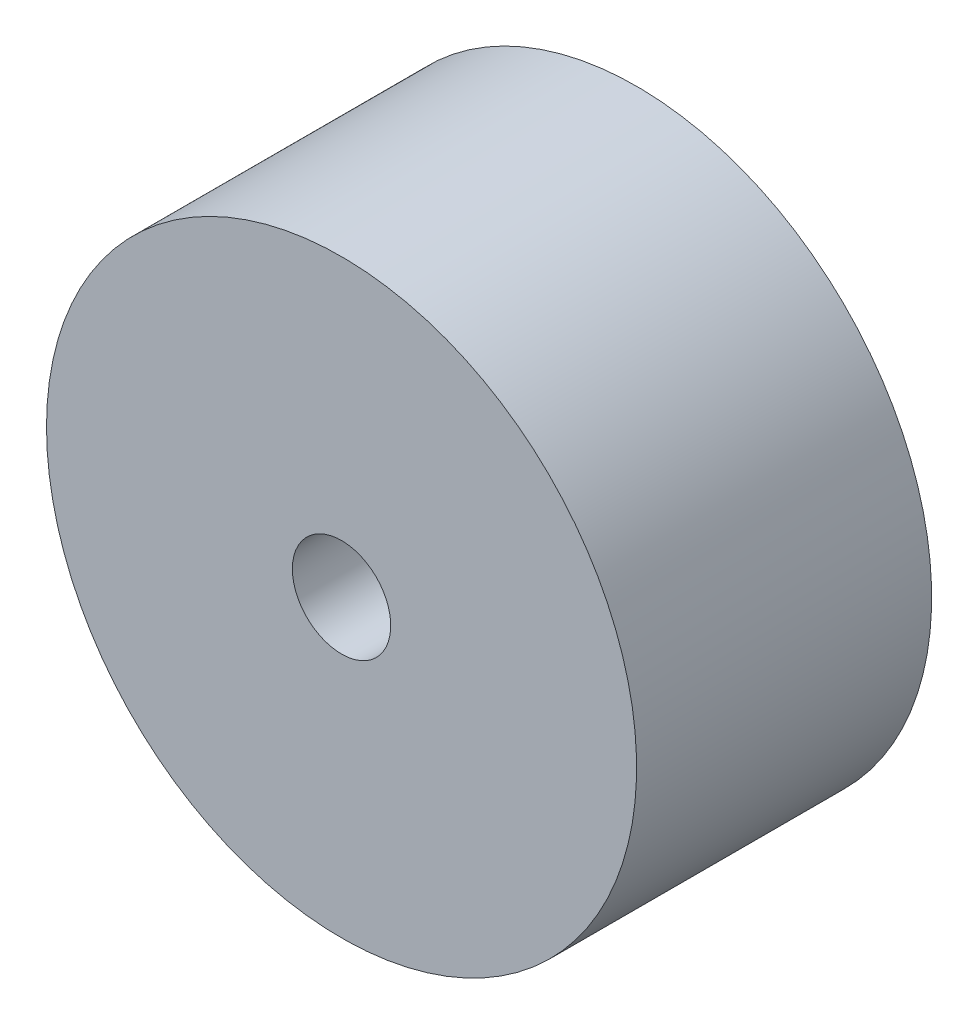
SolidWorks part; units mm, degrees
ref_plane "Plan de face" through (0, 0, 0) normal (0, 0, 1) x (1, 0, 0)
ref_plane "Plan de dessus" through (0, 0, 0) normal (0, 1, 0) x (1, 0, 0)
ref_plane "Plan de droite" through (0, 0, 0) normal (1, 0, 0) x (0, 0, -1)
sketch "Esquisse1" plane through (0, 0, 0) normal (0, 0, 1) x (1, 0, 0)
  circle A0 centre (0, 0) radius 38.1
  circle A1 centre (0, 0) radius 6.35
  dimension "D1" = 12.7
  dimension "D2" = 76.2
extrude "Boss.-Extru.1" add sketch "Esquisse1" along normal blind 38.1
